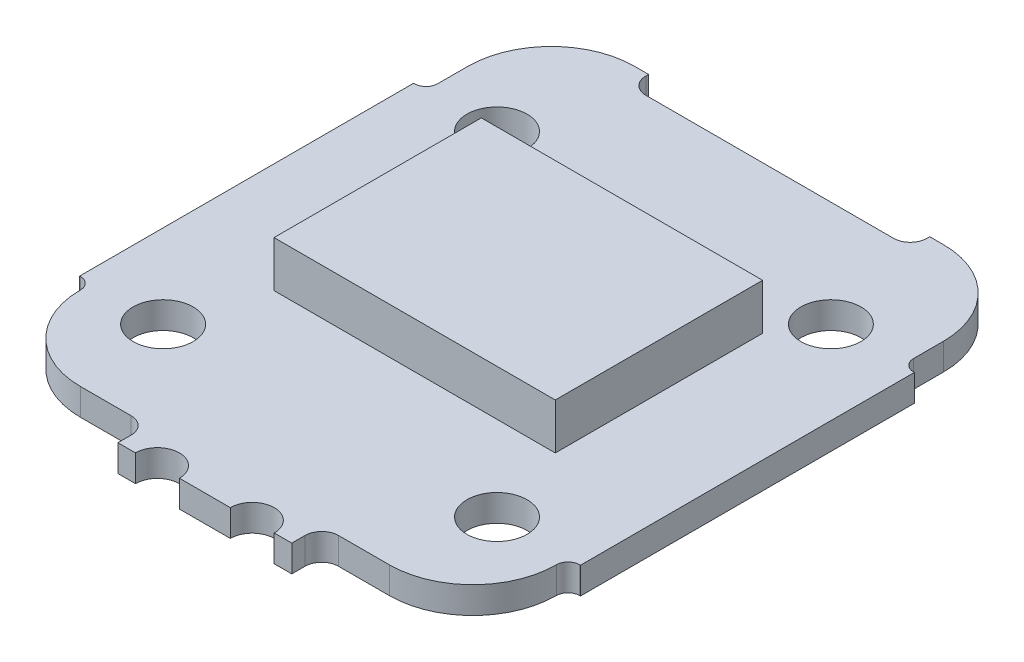
SolidWorks part; units mm, degrees
ref_plane "Front Plane" through (0, 0, 0) normal (0, 0, 1) x (1, 0, 0)
ref_plane "Top Plane" through (0, 0, 0) normal (0, 1, 0) x (1, 0, 0)
ref_plane "Right Plane" through (0, 0, 0) normal (1, 0, 0) x (0, 0, -1)
sketch "Sketch1" plane through (0, 0, 0) normal (0, 1, 0) x (1, 0, 0)
  line L1 (5206.9128, -17500) -> (4155.7889, -17500)
  line L2 (15000, -10000) -> (15000, 10000)
  line L3 (9252.7864, 17500) -> (8419.3177, 17500)
  line L4 (-15000, -10000) -> (-15000, 10000)
  line L5 (15000, -17500) -> (-15000, 17500) construction
  line L6 (15000, 17500) -> (-15000, -17500) construction
  line L7 (10000, -10000) -> (-10000, -10000) construction
  line L8 (10000, -10000) -> (10000, 10000) construction
  line L9 (10000, 10000) -> (-10000, 10000) construction
  line L10 (-10000, -10000) -> (-10000, 10000) construction
  line L11 (10000, -10000) -> (-10000, 10000) construction
  line L12 (10000, 10000) -> (-10000, -10000) construction
  line L13 (7419.3177, 16333.6897) -> (-7419.3177, 16333.6897)
  line L14 (-8419.3177, 17333.6897) -> (-8419.3177, 17500)
  line L15 (-14252.7864, 12500) -> (-14252.7864, 10700)
  line L16 (-14952.7864, 10000) -> (-15000, 10000)
  line L17 (-15000, -10000) -> (-14952.7864, -10000)
  line L18 (-14252.7864, -10700) -> (-14252.7864, -10704.4146)
  line L19 (-5206.9128, -17500) -> (-5206.9128, -16704.4146)
  line L20 (-6206.9128, -15704.4146) -> (-9252.7864, -15704.4146)
  line L21 (-8419.3177, 17500) -> (-9252.7864, 17500)
  line L22 (5206.9128, -17500) -> (5206.9128, -16704.4146)
  line L23 (6206.9128, -15704.4146) -> (9252.7864, -15704.4146)
  line L24 (14252.7864, -10700) -> (14252.7864, -10704.4146)
  line L25 (15000, -10000) -> (14952.7864, -10000)
  line L26 (14952.7864, 10000) -> (15000, 10000)
  line L27 (14252.7864, 12500) -> (14252.7864, 10700)
  line L28 (8419.3177, 17333.6897) -> (8419.3177, 17500)
  line L29 (0, 0) -> (0, -13681.2604) construction
  line L30 (-4155.7889, -17500) -> (-5206.9128, -17500)
  line L31 (1524.7462, -17500) -> (-1524.7462, -17500)
  arc A0 (-9252.7864, -15704.4146) -> (-14252.7864, -10704.4146) centre (-9252.7864, -10704.4146) cw
  arc A1 (9252.7864, -15704.4146) -> (14252.7864, -10704.4146) centre (9252.7864, -10704.4146) ccw
  arc A2 (14252.7864, 12500) -> (9252.7864, 17500) centre (9252.7864, 12500) ccw
  arc A3 (-14252.7864, 12500) -> (-9252.7864, 17500) centre (-9252.7864, 12500) cw
  arc A4 (-5206.9128, -16704.4146) -> (-6206.9128, -15704.4146) centre (-6206.9128, -16704.4146) ccw
  arc A5 (5206.9128, -16704.4146) -> (6206.9128, -15704.4146) centre (6206.9128, -16704.4146) cw
  arc A6 (8419.3177, 17333.6897) -> (7419.3177, 16333.6897) centre (7419.3177, 17333.6897) cw
  arc A7 (-7419.3177, 16333.6897) -> (-8419.3177, 17333.6897) centre (-7419.3177, 17333.6897) cw
  arc A8 (-14952.7864, -10000) -> (-14252.7864, -10700) centre (-14952.7864, -10700) cw
  arc A9 (-14252.7864, 10700) -> (-14952.7864, 10000) centre (-14952.7864, 10700) cw
  arc A10 (14952.7864, 10000) -> (14252.7864, 10700) centre (14952.7864, 10700) cw
  arc A11 (14252.7864, -10700) -> (14952.7864, -10000) centre (14952.7864, -10700) cw
  arc A12 (-1524.7462, -17500) -> (-4155.7889, -17500) centre (-2840.2675, -17500) ccw
  arc A13 (1524.7462, -17500) -> (4155.7889, -17500) centre (2840.2675, -17500) cw
  circle A14 centre (10000, -10000) radius 1800
  circle A15 centre (-10000, -10000) radius 1800
  circle A16 centre (-10000, 10000) radius 1800
  circle A17 centre (10000, 10000) radius 1800
  point P0 (0, 0)
  point P6 (0, 0)
  dimension "D5" = 5000
  dimension "D6" = 1000
  dimension "D7" = 700
  dimension "D1" = 30000
  dimension "D2" = 35000
  dimension "D3" = 20000
  dimension "D4" = 20000
extrude "Boss-Extrude1" add sketch "Sketch1" along normal blind 1600
scale "Scale1" scale about centroid uniform scaling yes scale factor 0.001
sketch "Sketch2" plane through (0, 800.8, 0) normal (0, 1, 0) x (1, 0, 0)
  line L2 (-8.4238, 315.3942) -> (8.4238, 315.3942)
  line L3 (-8.4238, 315.3942) -> (-8.4238, 302.9751)
  line L4 (-8.4238, 302.9751) -> (8.4238, 302.9751)
  line L5 (8.4238, 315.3942) -> (8.4238, 302.9751)
  line L6 (-8.4238, 315.3942) -> (8.4238, 302.9751) construction
  line L7 (-8.4238, 302.9751) -> (8.4238, 315.3942) construction
  point P2 (0, 309.1847)
extrude "Boss-Extrude2" add sketch "Sketch2" along normal mid plane 5.5
